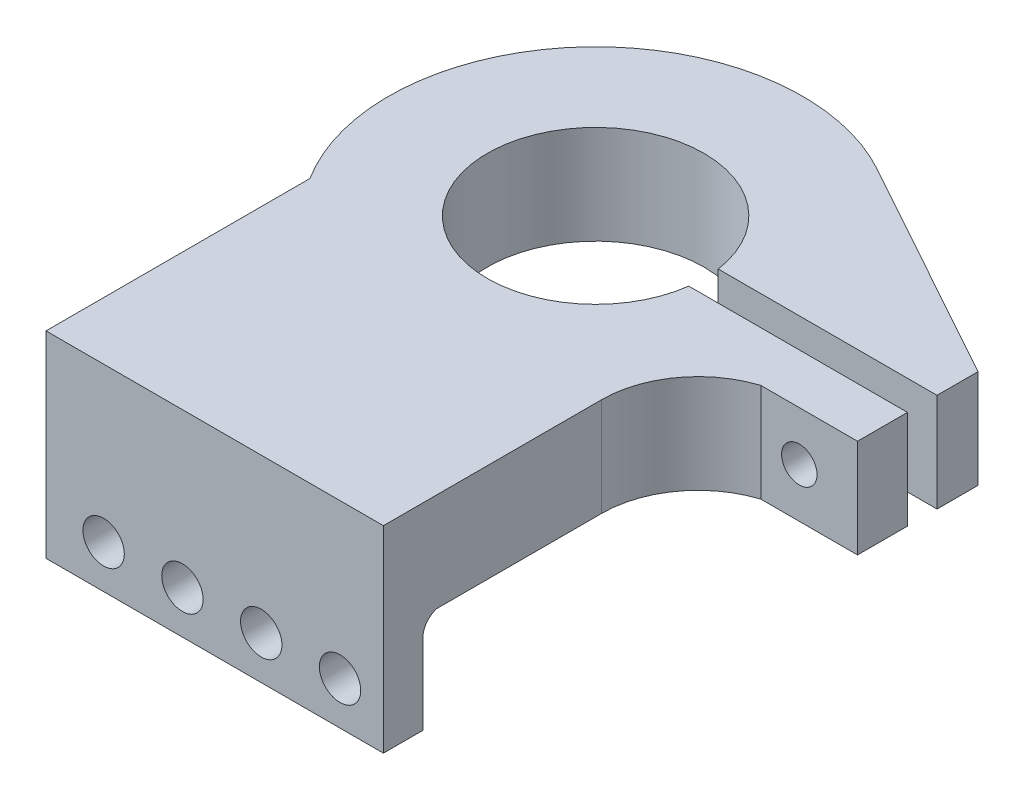
SolidWorks part; units mm, degrees
ref_plane "前基準面" through (0, 0, 0) normal (0, 0, 1) x (1, 0, 0)
ref_plane "上基準面" through (0, 0, 0) normal (0, 1, 0) x (1, 0, 0)
ref_plane "右基準面" through (0, 0, 0) normal (1, 0, 0) x (0, 0, -1)
sketch "草圖1" plane through (0, 0, 0) normal (0, 1, 0) x (1, 0, 0)
  circle A0 centre (0, 0) radius 27
  circle A1 centre (0, 0) radius 11
extrude "填料-伸長1" add sketch "草圖1" along normal blind 10
sketch "草圖2" plane through (0, 10, 0) normal (0, 1, 0) x (1, 0, 0)
  line L9 (8.7542, 1.5531) -> (30.8493, 1.5531)
  line L10 (8.7542, 1.5531) -> (8.7542, -1.4469)
  line L11 (8.7542, -1.4469) -> (30.8493, -1.4469)
  line L12 (30.8493, 1.5531) -> (30.8493, -1.4469)
extrude "除料-伸長5" cut sketch "草圖2" against normal blind 10
sketch "草圖3" plane through (0, 10, 0) normal (0, 1, 0) x (1, 0, 0)
  line L1 (26.9553, 1.5531) -> (36.7749, 1.5531)
  line L2 (36.7749, 6.233) -> (36.7749, 1.5531)
  line L4 (36.7749, 6.233) -> (16.1568, 21.6323)
  line L5 (16.1568, 21.6323) -> (26.9553, 1.5531)
  arc A3 (26.9553, 1.5531) -> (26.9612, -1.4469) centre (0, 0) ccw construction
  dimension "D1" = 9.8196
extrude "填料-伸長6" add sketch "草圖3" against normal blind 10
sketch "草圖4" plane through (0, 10, 0) normal (0, 1, 0) x (1, 0, 0)
  line L0 (26.9612, -1.4469) -> (36.7712, -1.4469)
  line L1 (36.7712, -1.4469) -> (36.7712, -38.0028)
  line L2 (36.7712, -38.0028) -> (-26.9588, -38.0028)
  line L3 (-26.9588, -38.0028) -> (-27, 0)
  line L4 (-27, 0) -> (-10.9999, -0.0536)
  line L5 (-10.9999, -0.0536) -> (-10.9999, -22.1415)
  line L6 (-10.9999, -22.1415) -> (17.2393, -20.78)
  line L7 (17.2393, -20.78) -> (26.9612, -1.4469)
  arc A0 (16.1568, 21.6323) -> (26.9612, -1.4469) centre (0, 0) ccw construction
  arc A1 (10.8898, 1.5531) -> (10.9044, -1.4469) centre (0, 0) ccw construction
  dimension "D1" = 63.73
extrude "填料-伸長7" add sketch "草圖4" against normal blind 10
sketch "草圖5" plane through (0, 10, 0) normal (0, 1, 0) x (1, 0, 0)
  line L0 (36.7712, -1.4469) -> (36.7712, -6.1269)
  line L1 (36.7712, -38.0028) -> (36.7712, -1.4469) construction
  line L2 (36.7712, -6.1269) -> (26.7712, -6.1269)
  line L3 (26.7712, -6.1269) -> (26.7712, -38.0028)
  line L4 (-26.9588, -38.0028) -> (36.7712, -38.0028) construction
  line L5 (26.7712, -38.0028) -> (36.7712, -38.0028)
  line L6 (36.7712, -38.0028) -> (36.7712, -6.1269)
  line M11 (-26.9588, -38.0028) -> (36.7712, -38.0028)
  line M12 (36.7712, -38.0028) -> (36.7712, -1.4469)
  dimension "D1" = 10
extrude "除料-伸長6" cut sketch "草圖5" against normal blind 10 contours L2 L3 M11 M12
sketch "草圖6" plane through (0, 10, 0) normal (0, 1, 0) x (1, 0, 0)
  line L0 (28.5703, -6.1269) -> (26.7712, -6.1269)
  line L1 (36.7712, -6.1269) -> (26.7712, -6.1269) construction
  line L2 (26.7712, -6.1269) -> (26.7712, -8.915)
  line L3 (26.7712, -6.1269) -> (26.7712, -38.0028) construction
  arc A0 (26.7712, -8.915) -> (28.5703, -6.1269) centre (29.8311, -8.915) cw
extrude "填料-伸長8" add sketch "草圖6" against normal blind 10
sketch "草圖7" plane through (0, 0, 6.1269) normal (0, 0, 1) x (1, 0, 0)
  line L1 (36.7712, 10) -> (31.7712, 10)
  line L2 (36.7712, 10) -> (36.7712, 5)
  circle A0 centre (31.7712, 5) radius 1.8
extrude "除料-伸長7" cut sketch "草圖7" against normal blind 25 contours A0
sketch "草圖9" plane through (0, 0, 6.1269) normal (0, 0, 1) x (1, 0, 0)
  circle A0 centre (31.7712, 5) radius 3
extrude "除料-伸長8" cut sketch "草圖9" against normal blind 25
sketch "草圖10" plane through (0, 0, 6.1269) normal (0, 0, 1) x (1, 0, 0)
  circle A0 centre (31.7712, 5) radius 1.8
  circle A1 centre (31.7712, 5) radius 3
extrude "填料-伸長9" add sketch "草圖10" against normal blind 10
sketch "草圖11" plane through (0, 10, 0) normal (0, 1, 0) x (1, 0, 0)
  line L0 (36.7749, 1.5531) -> (10.8898, 1.5531) construction
  line L1 (34.8868, 1.5531) -> (28.5348, 1.5531)
  line L2 (34.8868, 1.5531) -> (34.8868, -1.4469)
  line L3 (34.8868, -1.4469) -> (28.5348, -1.4469)
  line L4 (28.5348, 1.5531) -> (28.5348, -1.4469)
  line L5 (10.9044, -1.4469) -> (36.7712, -1.4469) construction
extrude "除料-伸長9" cut sketch "草圖11" against normal blind 10
sketch "草圖12" plane through (0, 10, 0) normal (0, 1, 0) x (1, 0, 0)
  line L1 (-26.9588, -38.0028) -> (-22.9588, -38.0028)
  line L2 (-26.9588, -38.0028) -> (-26.9588, -1.9161)
  line L3 (-26.9588, -1.9161) -> (-22.9588, -1.9161)
  line L4 (-22.9588, -38.0028) -> (-22.9588, -1.9161)
  circle A0 centre (0, 0) radius 27
  line M10 (-26.9588, -38.0028) -> (26.7712, -38.0028)
  dimension "D1" = 4
extrude "除料-伸長11" cut sketch "草圖12" against normal blind 10 contours A0 L3 L2 L4 M10
sketch "草圖19" plane through (0, 10, 0) normal (0, 1, 0) x (1, 0, 0)
  line L0 (-26.9999, -0.0585) -> (-26.9588, -38.0028) construction
  line L1 (-26.9983, -1.5597) -> (-14.4077, -1.5597)
  line L2 (-26.9983, -1.5597) -> (-26.9983, -38.0028)
  line L3 (-26.9983, -38.0028) -> (-14.4077, -38.0028)
  line L4 (-14.4077, -1.5597) -> (-14.4077, -38.0028)
  line L5 (-22.9588, -38.0028) -> (26.7712, -38.0028) construction
extrude "填料-伸長10" add sketch "草圖19" against normal blind 10
sketch "草圖20" plane through (0, 10, 0) normal (0, 1, 0) x (1, 0, 0)
  line L0 (-18.65, -38.0028) -> (-18.65, -19.531)
  line L1 (-26.9983, -38.0028) -> (26.7712, -38.0028) construction
  line L2 (-18.65, -38.0028) -> (-29.65, -38.0028)
  line L3 (-29.65, -38.0028) -> (-29.65, 0)
  line L4 (-29.65, 0) -> (-26.9999, -0.0585)
  circle A0 centre (0, 0) radius 27.0053
  line M1 (-26.9999, -0.0585) -> (-26.9983, -1.5597)
  line M2 (-26.9983, -1.5597) -> (-26.9983, -38.0028)
  line M3 (-26.9983, -38.0028) -> (26.7712, -38.0028)
  dimension "D1" = 11
extrude "除料-伸長16" cut sketch "草圖20" against normal blind 45.4 contours A0 L4 L3 L2 M2 M1 | A0 L0 M1 M2 M3
sketch "草圖23" plane through (26.7712, 0, 0) normal (1, 0, 0) x (0, 0, -1)
  line L1 (-38.0028, 0) -> (-34.0028, 0)
  line L2 (-38.0028, 0) -> (-38.0028, -10)
  line L3 (-38.0028, -10) -> (-34.0028, -10)
  line L4 (-34.0028, 0) -> (-34.0028, -10)
extrude "填料-伸長14" add sketch "草圖23" against normal blind 45.5
sketch "草圖24" plane through (0, 10, 0) normal (0, 1, 0) x (1, 0, 0)
  line L0 (-18.65, -38.0028) -> (26.7712, -38.0028) construction
  line L1 (-18.65, -38.0028) -> (-22.875, -38.0028)
  line L2 (-18.65, -38.0028) -> (-18.65, -17.1671)
  line L3 (-18.65, -17.1671) -> (-22.875, -17.1671)
  line L4 (-22.875, -38.0028) -> (-22.875, -17.1671)
  line L5 (-18.65, -38.0028) -> (-18.65, -34.0028) construction
  circle A0 centre (0, 0) radius 27.0053
  arc M2 (-26.9994, -0.5631) -> (-18.65, -19.531) centre (0, 0) ccw
  line M3 (-18.65, -19.531) -> (-18.65, -38.0028)
extrude "除料-伸長17" cut sketch "草圖24" against normal blind 45.5 contours L4 L1 L3 M3 M2
sketch "草圖25" plane through (26.7712, 0, 0) normal (1, 0, 0) x (0, 0, -1)
  line L0 (-34.0028, -1.5638) -> (-34.0028, 0)
  line L1 (-34.0028, -10) -> (-34.0028, 0) construction
  line L2 (-34.0028, 0) -> (-32.5814, 0)
  line L3 (-8.915, 0) -> (-34.0028, 0) construction
  arc A0 (-32.5814, 0) -> (-34.0028, -1.5638) centre (-32.5814, -1.4279) ccw
  line M6 (-34.0028, 0) -> (-8.915, 0)
extrude "填料-伸長15" add sketch "草圖25" against normal blind 45.5 contours A0 L0 M6
sketch "草圖26" plane through (0, 0, 38.0028) normal (0, 0, 1) x (1, 0, 0)
  line L1 (-18.65, 0) -> (-18.9788, 0)
  line L2 (-18.65, 0) -> (-18.65, -1.3462)
  line L3 (-18.65, -1.3462) -> (-18.9788, -1.3462)
  line L4 (-18.9788, 0) -> (-18.9788, -1.3462)
extrude "除料-伸長18" cut sketch "草圖26" against normal blind 45.5
sketch "草圖28" plane through (0, 10, 0) normal (0, 1, 0) x (1, 0, 0)
  circle A7 centre (0, 19.5684) radius 2.5
  circle A8 centre (10, 17.0684) radius 2.5
  circle A9 centre (-10.0037, 17.0684) radius 2.5
  circle A10 centre (-18.4887, 0) radius 2.5
  circle A11 centre (-15.9887, 10.0294) radius 2.5
  circle A12 centre (-15.9887, -10.0544) radius 2.5
  circle A13 centre (15.383, 10.0294) radius 2.5
extrude "除料-伸長19" cut sketch "草圖28" against normal blind 45.5
sketch "草圖30" plane through (0, 0, 34.0028) normal (0, 0, -1) x (-1, 0, 0)
  line L2 (18.65, -10) -> (18.65, -1.292)
  line L3 (18.65, -1.292) -> (-26.7712, -1.292)
  line L4 (-26.7712, -10) -> (-26.7712, -1.292)
  circle A0 centre (-4.0606, -5.646) radius 1.8
  circle A1 centre (-12.0606, -5.646) radius 1.8
  circle A2 centre (-20.0606, -5.646) radius 1.8
  circle A3 centre (3.9394, -5.646) radius 1.8
  circle A4 centre (11.9394, -5.646) radius 1.8
extrude "除料-伸長21" cut sketch "草圖30" against normal blind 45.5 contours A3 | A0 | A1 | A2 | A4
sketch "草圖31" plane through (0, 10, 0) normal (0, 1, 0) x (1, 0, 0)
  line L1 (-19.6137, -14.5942) -> (-11.9095, -14.5942)
  line L2 (-19.6137, -14.5942) -> (-19.6137, 13.2664)
  line L3 (-19.6137, 13.2664) -> (-11.9095, 13.2664)
  line L4 (-11.9095, -14.5942) -> (-11.9095, 13.2664)
  line L5 (-24.0033, 10.3102) -> (-15.7616, 10.3102)
  line L6 (-24.0033, 10.3102) -> (-24.0033, -4.6504)
  line L7 (-24.0033, -4.6504) -> (-15.7616, -4.6504)
  line L8 (-15.7616, 10.3102) -> (-15.7616, -4.6504)
  line L9 (-15.7616, 21.9219) -> (15.4136, 21.9219)
  line L10 (-15.7616, 21.9219) -> (-15.7616, 11.2956)
  line L11 (-15.7616, 11.2956) -> (15.4136, 11.2956)
  line L12 (15.4136, 21.9219) -> (15.4136, 11.2956)
  line L13 (-2.5032, 23.5686) -> (1.5281, 23.5686)
  line L14 (-2.5032, 23.5686) -> (-2.5032, 20.6123)
  line L15 (-2.5032, 20.6123) -> (1.5281, 20.6123)
  line L16 (1.5281, 23.5686) -> (1.5281, 20.6123)
  line L17 (10.255, 16.6082) -> (19.1238, 16.6082)
  line L18 (10.255, 16.6082) -> (10.255, 5.6513)
  line L19 (10.255, 5.6513) -> (19.1238, 5.6513)
  line L20 (19.1238, 16.6082) -> (19.1238, 5.6513)
  arc A0 (16.1568, 21.6323) -> (-26.9999, -0.0585) centre (0, 0) ccw construction
  circle M1 centre (10, 17.0684) radius 2.5
  circle M2 centre (0, 19.5684) radius 2.5
  circle M3 centre (-15.9887, 10.0294) radius 2.5
  circle M5 centre (-15.9887, -10.0544) radius 2.5
  circle M6 centre (15.383, 10.0294) radius 2.5
  circle M7 centre (-10.0037, 17.0684) radius 2.5
extrude "填料-伸長16" add sketch "草圖31" against normal blind 10 contours L18 L17 L12 L9 L16 L15 L14 L10 L3 L4 L11 M1 M2 M7 | M7 | L18 L17 M1 | L18 L11 L12 L17 M1 M6 | L17 L18 M1 | L12 L11 M6 | L20 L17 L12 L11 L18 L19 M6 | L11 L8 L7 L2 L1 L4 M3 M5 | L11 L10 L5 L8 M3 | L10 L3 L2 L5 M3 | M5
sketch "草圖32" plane through (0, 0, 0) normal (0, -1, 0) x (-1, 0, 0)
  line L0 (18.65, -32.5814) -> (-26.7712, -32.5814) construction
  line L2 (7.7869, -32.5814) -> (7.7869, -19.531)
  line L3 (7.7869, -19.531) -> (18.65, -19.531)
  line L4 (18.65, -32.5814) -> (18.65, -19.531)
  line L7 (7.7869, -32.5814) -> (7.7869, -42.5048)
  line L10 (18.65, -32.5814) -> (18.65, -42.5048)
  line L11 (18.65, -42.5048) -> (7.7869, -42.5048)
extrude "除料-伸長23" cut sketch "草圖32" against normal blind 10 and the other way blind 10
sketch "草圖33" plane through (0, 0, 0) normal (0, -1, 0) x (-1, 0, 0)
  line L0 (-14.3572, 15.3612) -> (-21.1397, 22.6179)
  line L1 (-21.1397, 22.6179) -> (1.281, 36.7753)
  line L2 (1.281, 36.7753) -> (35.7031, 9.0038)
  line L3 (35.7031, 9.0038) -> (17.7527, -25.2748)
  line L4 (17.7527, -25.2748) -> (7.7869, -19.531)
  arc A0 (7.7869, -19.531) -> (-14.3572, 15.3612) centre (0, 0) ccw
extrude "除料-伸長24" cut sketch "草圖33" against normal blind 10
sketch "草圖34" plane through (0, 0, 0) normal (0, -1, 0) x (-1, 0, 0)
  line L0 (-14.3572, 15.3612) -> (-36.7749, 6.233)
  line L1 (-36.7749, 6.233) -> (-37.2764, 15.8611)
  line L2 (-37.2764, 15.8611) -> (-16.5525, 23.3004)
  line L3 (-16.5525, 23.3004) -> (-14.3572, 15.3612)
extrude "除料-伸長25" cut sketch "草圖34" against normal blind 10
sketch "草圖35" plane through (0, 0, 0) normal (0, -1, 0) x (-1, 0, 0)
  line L2 (-26.7712, -32.5814) -> (-26.7712, -8.915)
  circle A1 centre (0, 16.0389) radius 2.5
  circle A2 centre (11.3412, 11.3412) radius 2.5
  circle A3 centre (16.0389, 0) radius 2.5
  circle A4 centre (11.3412, -11.3412) radius 2.5
  circle A5 centre (0, -16.0389) radius 2.5
  circle A6 centre (-11.3412, -11.3412) radius 2.5
  circle A8 centre (-11.3412, 11.3412) radius 2.5
  circle A9 centre (-16.0389, 0) radius 2.5 [skipped]
  dimension "D1" = 8
extrude "除料-伸長26" cut sketch "草圖35" against normal blind 10 contours A8 | A1 | A2 | A3 | A4 | A5 | A6
sketch "草圖36" plane through (0, 0, 0) normal (0, -1, 0) x (-1, 0, 0)
  line L0 (7.7869, -32.5814) -> (-26.7712, -32.5814) construction
  line L1 (-16.4615, -32.5814) -> (-29.2458, -32.5814)
  line L2 (-16.4615, -32.5814) -> (-16.4615, -48.7321)
  line L3 (-16.4615, -48.7321) -> (-29.2458, -48.7321)
  line L4 (-29.2458, -32.5814) -> (-29.2458, -48.7321)
  line L5 (-16.4615, -32.5814) -> (-16.4615, -15.8401)
  line L6 (-26.2436, -6.0579) -> (-36.7712, -6.0579)
  line L7 (-36.7712, -6.1269) -> (-36.7712, -1.4469) construction
  line L8 (-36.7712, -6.0579) -> (-36.7712, -32.5814)
  line L9 (-36.7712, -32.5814) -> (-29.2458, -32.5814)
  arc A0 (-16.4615, -15.8401) -> (-26.2436, -6.0579) centre (-26.2436, -15.8401) ccw
  line M14 (-36.7712, -1.4469) -> (-36.7712, -6.1269)
  line M15 (-36.7712, -6.1269) -> (-28.5703, -6.1269)
  arc M16 (-28.5703, -6.1269) -> (-26.7712, -8.915) centre (-29.8311, -8.915) cw
  line M17 (-26.7712, -8.915) -> (-26.7712, -32.5814)
  line M18 (-26.7712, -32.5814) -> (7.7869, -32.5814)
extrude "除料-伸長28" cut sketch "草圖36" along normal up to surface and the other way blind 10 contours L8 L9 L1 M17 M16 M15 | L5 A0 L6 M14 M15 M16 M17 M18 | L1 L4 L3 L2 M18 up to face at (9.4922, -10, 36.0028)
sketch "草圖38" plane through (-7.7869, 0, 0) normal (-1, 0, 0) x (0, 0, 1)
  line L0 (19.531, 0) -> (19.531, 10)
  line L1 (19.531, 10) -> (38.0028, 10)
  line L2 (38.0028, 10) -> (38.0028, -10)
  line L3 (38.0028, -10) -> (34.0028, -10)
  line L4 (34.0028, -10) -> (34.0028, -1.292)
  line L5 (32.5814, 0) -> (19.531, 0)
  arc A0 (34.0028, -1.292) -> (32.5814, 0) centre (32.705, -1.292) ccw
extrude "填料-伸長17" add sketch "草圖38" along normal blind 10
sketch "草圖40" plane through (-17.7869, 0, 0) normal (-1, 0, 0) x (0, 0, 1)
  line L0 (34.0028, -1.889) -> (37.1817, -1.889)
  line L1 (34.0028, -1.292) -> (34.0028, -10) construction
  line L2 (37.1817, -1.889) -> (35.3742, 3.5989)
  line L3 (35.3742, 3.5989) -> (31.0817, 2.185)
  line L4 (31.0817, 2.185) -> (32.5814, 0)
  arc A0 (34.0028, -1.889) -> (32.5814, 0) centre (32.037, -1.889) ccw
extrude "填料-伸長18" add sketch "草圖40" against normal blind 35
sketch "草圖41" plane through (16.4615, 0, 0) normal (1, 0, 0) x (0, 0, -1)
  line L0 (-38.0028, 10) -> (-38.0028, -10) construction
  line L1 (-38.0028, 7.7686) -> (-27.4132, 7.7686)
  line L2 (-38.0028, 7.7686) -> (-38.0028, -11.2624)
  line L3 (-38.0028, -11.2624) -> (-27.4132, -11.2624)
  line L4 (-27.4132, 7.7686) -> (-27.4132, -11.2624)
extrude "除料-伸長29" cut sketch "草圖41" along normal blind 8
sketch "草圖42" plane through (0, 0, 0) normal (0, -1, 0) x (-1, 0, 0)
  line L0 (17.7869, -19.531) -> (17.7869, -11.2126)
  line L1 (17.7869, -11.2126) -> (7.7869, -19.531)
  line L2 (7.7869, -19.531) -> (17.7869, -19.531)
  arc A0 (7.7869, -19.531) -> (-14.3572, 15.3612) centre (0, 0) ccw construction
extrude "填料-伸長19" add sketch "草圖42" against normal blind 10
sketch "草圖43" plane through (0, 10, 0) normal (0, 1, 0) x (1, 0, 0)
  line L0 (19.9906, -6.517) -> (36.7712, -6.517)
  line L1 (36.7712, -6.517) -> (36.7712, -1.4469)
  line L2 (36.7712, -1.4469) -> (36.7749, 6.233)
  line L3 (36.7749, 6.233) -> (14.3572, 15.3612)
  arc A0 (14.3572, 15.3612) -> (19.9906, -6.517) centre (0, 0) cw
extrude "除料-伸長30" cut sketch "草圖43" against normal blind 10
sketch "草圖44" plane through (36.7749, 0, 0) normal (1, 0, 0) x (0, 0, -1)
  line L1 (10.7408, 11.6279) -> (-1.321, 11.6279)
  line L2 (10.7408, 11.6279) -> (10.7408, -1.9202)
  line L3 (10.7408, -1.9202) -> (-1.321, -1.9202)
  line L4 (-1.321, 11.6279) -> (-1.321, -1.9202)
extrude "除料-伸長31" cut sketch "草圖44" against normal blind 10
sketch "草圖45" plane through (0, 10, 0) normal (0, 1, 0) x (1, 0, 0)
  line L0 (19.9906, -6.517) -> (31.1001, -6.517)
  line L1 (20.9762, -1.4469) -> (31.1001, -1.4469)
  line L2 (31.1001, -1.4469) -> (31.1001, -6.517)
  line L3 (10.1811, 18.3967) -> (31.1001, 6.8197)
  line L4 (20.9686, 1.5531) -> (31.1001, 1.5531)
  line L5 (31.1001, 1.5531) -> (31.1001, 6.8197)
  arc A0 (20.9762, -1.4469) -> (19.9906, -6.517) centre (0, 0) cw
  arc A1 (20.9686, 1.5531) -> (-17.7869, -11.2126) centre (0, 0) ccw construction
  arc A2 (20.9686, 1.5531) -> (10.1811, 18.3967) centre (0, 0) ccw
  arc M2 (20.9686, 1.5531) -> (-17.7869, -11.2126) centre (0, 0) ccw
  line M7 (23.282, -6.517) -> (19.9906, -6.517)
  arc M8 (19.9906, -6.517) -> (20.9762, -1.4469) centre (0, 0) ccw
extrude "填料-伸長20" add sketch "草圖45" against normal blind 10 contours L4 L5 L3 M2 | L2 L1 L0 M8 M7
sketch "草圖46" plane through (0, 0, 6.517) normal (0, 0, 1) x (1, 0, 0)
  circle A0 centre (27.1911, 5) radius 1.8
extrude "除料-伸長33" cut sketch "草圖46" against normal blind 27
sketch "草圖48" plane through (0, 0, -1.5531) normal (0, 0, 1) x (1, 0, 0)
  circle A0 centre (27.1911, 5) radius 4
extrude "除料-伸長34" cut sketch "草圖48" against normal blind 27
sketch "草圖49" plane through (31.1001, 0, 0) normal (1, 0, 0) x (0, 0, -1)
  line L1 (-6.517, 10) -> (6.8197, 10)
  line L2 (-6.517, 10) -> (-6.517, 0)
  line L3 (-6.517, 0) -> (6.8197, 0)
  line L4 (6.8197, 10) -> (6.8197, 0)
extrude "填料-伸長21" add sketch "草圖49" along normal blind 2
sketch "草圖52" plane through (0, 0, 0) normal (0, -1, 0) x (-1, 0, 0)
  line L0 (-29.3388, 7.7945) -> (-33.2951, 5.605)
  line L1 (-10.1811, 18.3967) -> (-31.1001, 6.8197) construction
  line L2 (-33.2951, 5.605) -> (-33.2951, 7.7945)
  line L3 (-33.2951, 7.7945) -> (-29.3388, 7.7945)
  line L4 (-31.1001, 1.5531) -> (-34.2135, 1.5531)
  line L5 (-31.1001, 1.5531) -> (-31.1001, -1.4469)
  line L6 (-31.1001, -1.4469) -> (-36.1309, -1.4469)
  line L7 (-36.1309, -1.4469) -> (-34.2135, 1.5531)
extrude "除料-伸長35" cut sketch "草圖52" against normal blind 14
sketch "草圖53" plane through (0, 0, 1.4469) normal (0, 0, -1) x (-1, 0, 0)
  circle A0 centre (-27.1911, 5) radius 4
  circle A1 centre (-27.1911, 5) radius 1.8
extrude "填料-伸長22" add sketch "草圖53" along normal blind 4
sketch "草圖54" plane through (0, 0, 0) normal (0, -1, 0) x (-1, 0, 0)
  line L0 (-10.9044, -1.4469) -> (-33.1001, -1.4469) construction
  line L1 (-33.1001, 1.5531) -> (-22.0023, 1.5531)
  line L2 (-33.1001, 1.5531) -> (-33.1001, -1.4469)
  line L3 (-33.1001, -1.4469) -> (-22.0023, -1.4469)
  line L4 (-22.0023, 1.5531) -> (-22.0023, -1.4469)
extrude "除料-伸長36" cut sketch "草圖54" against normal blind 11
sketch "草圖55" plane through (0, 0, 34.0028) normal (0, 0, -1) x (-1, 0, 0)
  line L0 (3.9394, -5.646) -> (11.9394, -5.646)
  circle A0 centre (11.9394, -5.646) radius 1.8
  dimension "D1" = 8
extrude "除料-伸長37" cut sketch "草圖55" against normal blind 10
sketch "草圖56" plane through (0, 10, 0) normal (0, 1, 0) x (1, 0, 0)
  circle A0 centre (11.3412, 11.3412) radius 2.5
  circle A2 centre (11.3412, -11.3412) radius 2.5
  circle A3 centre (0, -16.0389) radius 2.5
  circle A4 centre (-11.3412, -11.3412) radius 2.5
  circle A5 centre (-16.0389, 0) radius 2.5
  circle A6 centre (-11.3412, 11.3412) radius 2.5
  circle A7 centre (0, 16.0389) radius 2.5
  circle A8 centre (16.0389, 0) radius 2.5 [skipped]
  dimension "D1" = 8
extrude "填料-伸長23" add sketch "草圖56" against normal blind 0.5
sketch "草圖57" plane through (0, 0, 34.0028) normal (0, 0, -1) x (-1, 0, 0)
  circle A0 centre (11.9394, -5.646) radius 2.1
  circle A1 centre (3.9394, -5.646) radius 2.1
  circle A2 centre (-4.0606, -5.646) radius 2.1
  circle A3 centre (-12.0606, -5.646) radius 2.1
  dimension "D1" = 4.2
  dimension "D2" = 4
extrude "除料-伸長38" cut sketch "草圖57" against normal blind 10
